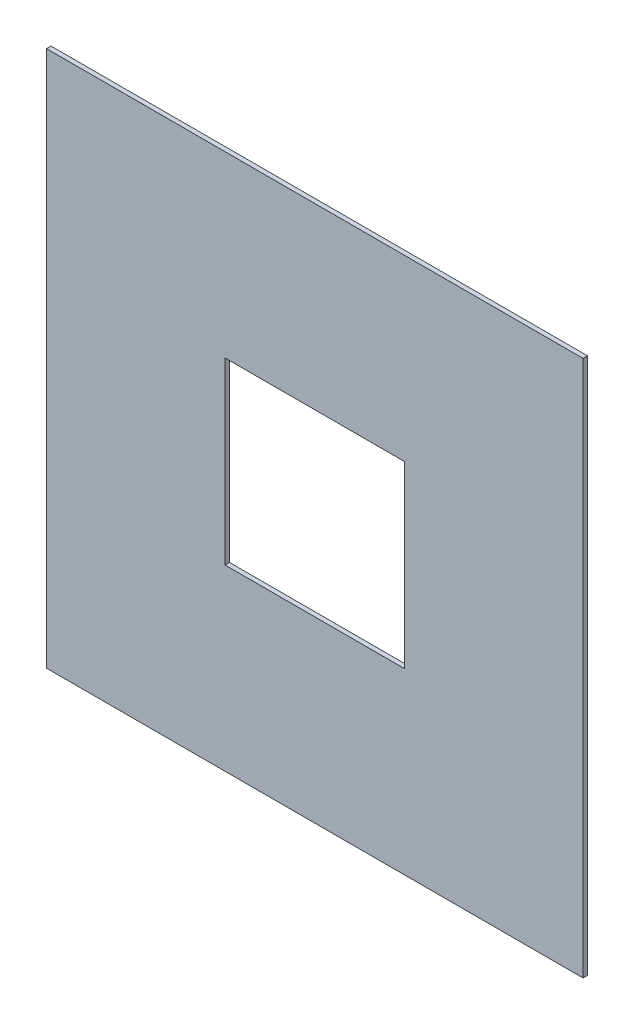
SolidWorks part; units mm, degrees
ref_plane "Front Plane" through (0, 0, 0) normal (0, 0, 1) x (1, 0, 0)
ref_plane "Top Plane" through (0, 0, 0) normal (0, 1, 0) x (1, 0, 0)
ref_plane "Right Plane" through (0, 0, 0) normal (1, 0, 0) x (0, 0, -1)
sketch "Sketch1" plane through (0, 0, 0) normal (0, 0, 1) x (1, 0, 0)
  line L1 (-60, 60) -> (60, 60)
  line L2 (-60, 60) -> (-60, -60)
  line L3 (-60, -60) -> (60, -60)
  line L4 (60, 60) -> (60, -60)
  line L5 (-60, 60) -> (60, -60) construction
  line L6 (-60, -60) -> (60, 60) construction
  line L7 (-20.05, 20.05) -> (20.05, 20.05)
  line L8 (-20.05, 20.05) -> (-20.05, -20.05)
  line L9 (-20.05, -20.05) -> (20.05, -20.05)
  line L10 (20.05, 20.05) -> (20.05, -20.05)
  line L11 (-20.05, 20.05) -> (20.05, -20.05) construction
  line L12 (-20.05, -20.05) -> (20.05, 20.05) construction
  point P0 (0, 0)
  point P6 (0, 0)
  dimension "D1" = 120
  dimension "D2" = 120
  dimension "D3" = 40.1
extrude "Boss-Extrude1" add sketch "Sketch1" along normal blind 1
